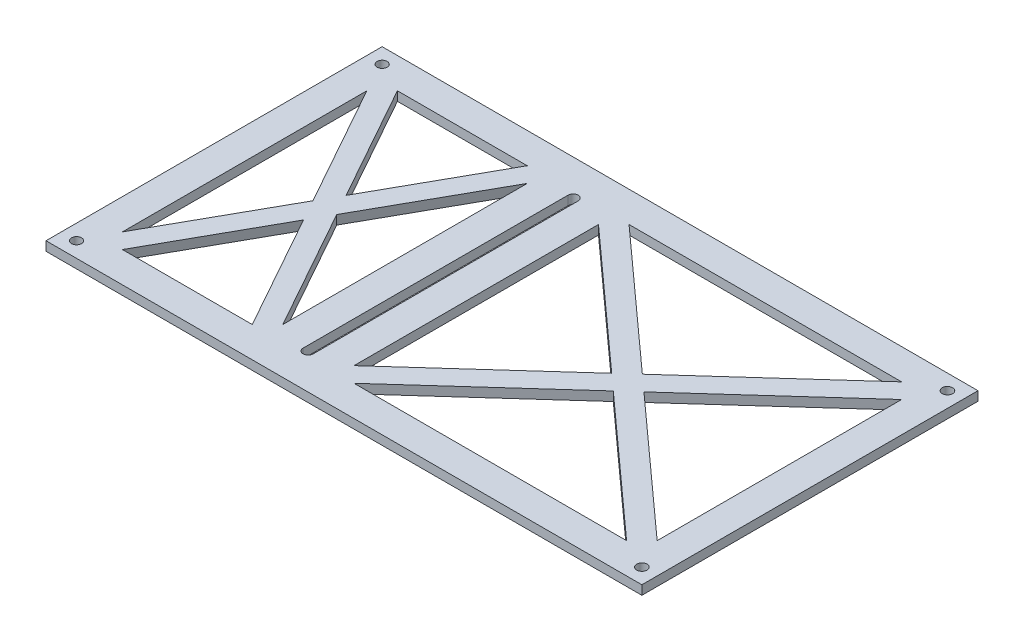
SolidWorks part; units mm, degrees
ref_plane "前视基准面" through (0, 0, 0) normal (0, 0, 1) x (1, 0, 0)
ref_plane "上视基准面" through (0, 0, 0) normal (0, 1, 0) x (1, 0, 0)
ref_plane "右视基准面" through (0, 0, 0) normal (1, 0, 0) x (0, 0, -1)
sketch "草图1" plane through (0, 0, 0) normal (0, 1, 0) x (1, 0, 0)
  line L0 (0, -21.0388) -> (0, 73.1943) construction
  line L1 (185, 83.3144) -> (185, -33.0322) construction
  line L3 (67.5, 6.65) -> (67.5, 93.35)
  line L5 (70.8, 6.65) -> (70.8, 93.35)
  line L6 (-5, -5) -> (190, -5)
  line L7 (-5, -5) -> (-5, 105)
  line L8 (-5, 105) -> (190, 105)
  line L9 (190, -5) -> (190, 105)
  line L10 (5, 90) -> (27.3529, 50)
  line L11 (10, 95) -> (52.5, 95)
  line L12 (5, 90) -> (5, 10)
  line L13 (10, 5) -> (52.5, 5)
  line L14 (57.5, 90) -> (57.5, 10)
  line L15 (85.8, 5) -> (175, 5)
  line L16 (80.8, 10) -> (80.8, 90)
  line L17 (85.8, 95) -> (175, 95)
  line L18 (180, 10) -> (180, 90)
  line L19 (10, 95) -> (31.25, 56.9737)
  line L20 (52.5, 95) -> (31.25, 56.9737)
  line L21 (57.5, 90) -> (35.1471, 50)
  line L22 (80.8, 90) -> (125.1294, 50)
  line L23 (180, 10) -> (135.6706, 50)
  line L24 (180, 90) -> (135.6706, 50)
  line L25 (175, 95) -> (130.4, 54.7558)
  line L26 (35.1471, 50) -> (57.5, 10)
  line L27 (27.3529, 50) -> (5, 10)
  line L28 (31.25, 43.0263) -> (10, 5)
  line L29 (31.25, 43.0263) -> (52.5, 5)
  line L30 (130.4, 54.7558) -> (85.8, 95)
  line L31 (130.4, 45.2442) -> (175, 5)
  line L32 (125.1294, 50) -> (80.8, 10)
  line L33 (130.4, 45.2442) -> (85.8, 5)
  circle A0 centre (0, 0) radius 1.65
  circle A1 centre (0, 100) radius 1.65
  circle A2 centre (185, 100) radius 1.7
  circle A3 centre (185, 0) radius 1.7
  arc A4 (70.8, 93.35) -> (67.5, 93.35) centre (69.15, 93.35) ccw
  arc A5 (67.5, 6.65) -> (70.8, 6.65) centre (69.15, 6.65) ccw
  dimension "D1" = 3.3
  dimension "D2" = 3.3
  dimension "D3" = 100
  dimension "D8" = 5
  dimension "D10" = 3.4
  dimension "D11" = 3.4
  dimension "D12" = 5
  dimension "D13" = 5
  dimension "D14" = 5
  dimension "D16" = 1.65
  dimension "D4" = 67.5
  dimension "D5" = 11.65
  dimension "D6" = 5
  dimension "D7" = 5
  dimension "D9" = 185
  dimension "D15" = 11.65
  dimension "D17" = 10
  dimension "D18" = 5
  dimension "D19" = 10
  dimension "D20" = 10
  dimension "D21" = 10
  dimension "D22" = 5
  dimension "D23" = 10
  dimension "D24" = 10
  dimension "D25" = 5
  dimension "D26" = 5
  dimension "D27" = 5
  dimension "D28" = 5
  dimension "D29" = 5
  dimension "D30" = 5
  dimension "D31" = 5
  dimension "D32" = 5
  dimension "D33" = 5
  dimension "D34" = 5
  dimension "D35" = 5
  dimension "D36" = 5
extrude "凸台-拉伸1" add sketch "草图1" along normal blind 3
